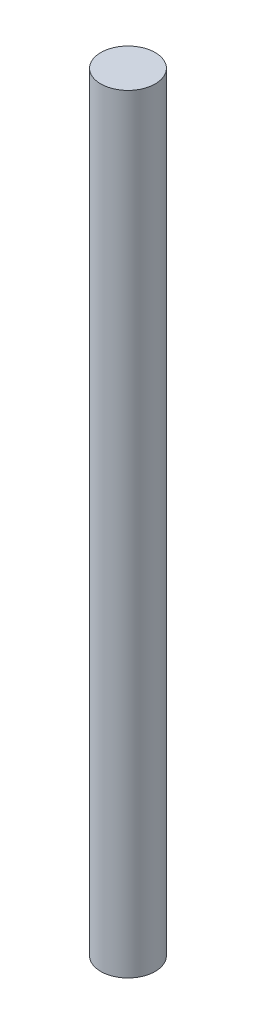
SolidWorks part; units mm, degrees
ref_plane "Płaszczyzna przednia" through (0, 0, 0) normal (0, 0, 1) x (1, 0, 0)
ref_plane "Płaszczyzna górna" through (0, 0, 0) normal (0, 1, 0) x (1, 0, 0)
ref_plane "Płaszczyzna prawa" through (0, 0, 0) normal (1, 0, 0) x (0, 0, -1)
sketch "Szkic1" plane through (0, 0, 0) normal (0, 1, 0) x (1, 0, 0)
  circle A0 centre (0, 0) radius 4
  dimension "D1" = 8
extrude "Dodanie-wyciągnięcie1" add sketch "Szkic1" along normal blind 113
